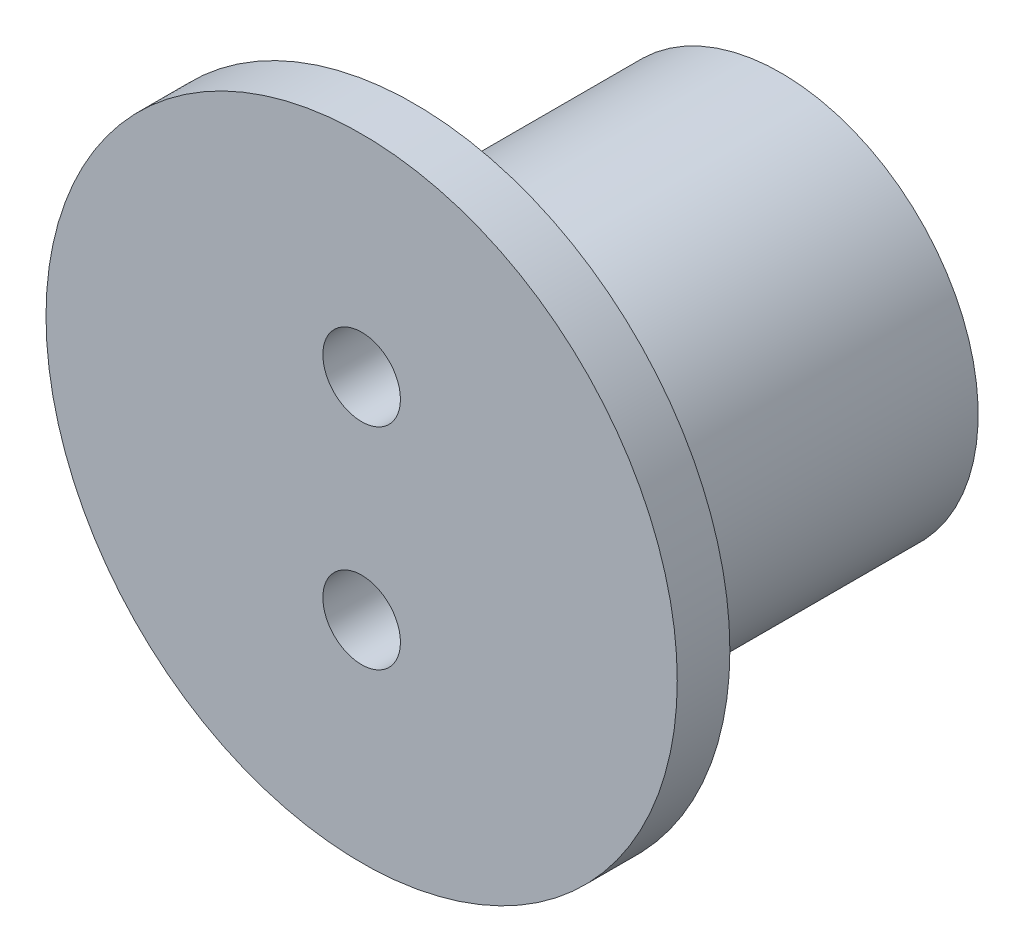
SolidWorks part; units mm, degrees
ref_plane "Front Plane" through (0, 0, 0) normal (0, 0, 1) x (1, 0, 0)
ref_plane "Top Plane" through (0, 0, 0) normal (0, 1, 0) x (1, 0, 0)
ref_plane "Right Plane" through (0, 0, 0) normal (1, 0, 0) x (0, 0, -1)
sketch "Sketch1" plane through (0, 0, 0) normal (0, 0, 1) x (1, 0, 0)
  circle A0 centre (0, 0) radius 12
  dimension "D1" = 24
extrude "Boss-Extrude2" add sketch "Sketch1" along normal blind 2
sketch "Sketch2" plane through (0, 0, 0) normal (0, 0, -1) x (-1, 0, 0)
  line L0 (0, 0) -> (3.935, 0)
  circle A0 centre (-1.9403, 0.4851) radius 7.5
  dimension "D1" = 15
  dimension "D2" = 2
extrude "Boss-Extrude3" add sketch "Sketch2" along normal blind 12
sketch "Sketch3" plane through (0, 0, 2) normal (0, 0, 1) x (1, 0, 0)
  circle A0 centre (0, 4) radius 1.35
  circle A1 centre (0, -4) radius 1.35
  dimension "D1" = 2.7
  dimension "D2" = 2.7
  dimension "D3" = 4
  dimension "D4" = 4
extrude "Cut-Extrude2" cut sketch "Sketch3" against normal through all
sketch "Sketch4" plane through (0, 0, 2) normal (0, 0, 1) x (1, 0, 0)
  circle A0 centre (0, 4) radius 1.475
  circle A1 centre (0, -4) radius 1.475
  dimension "D1" = 2.95
  dimension "D2" = 2.95
extrude "Cut-Extrude4" cut sketch "Sketch4" against normal blind 18
